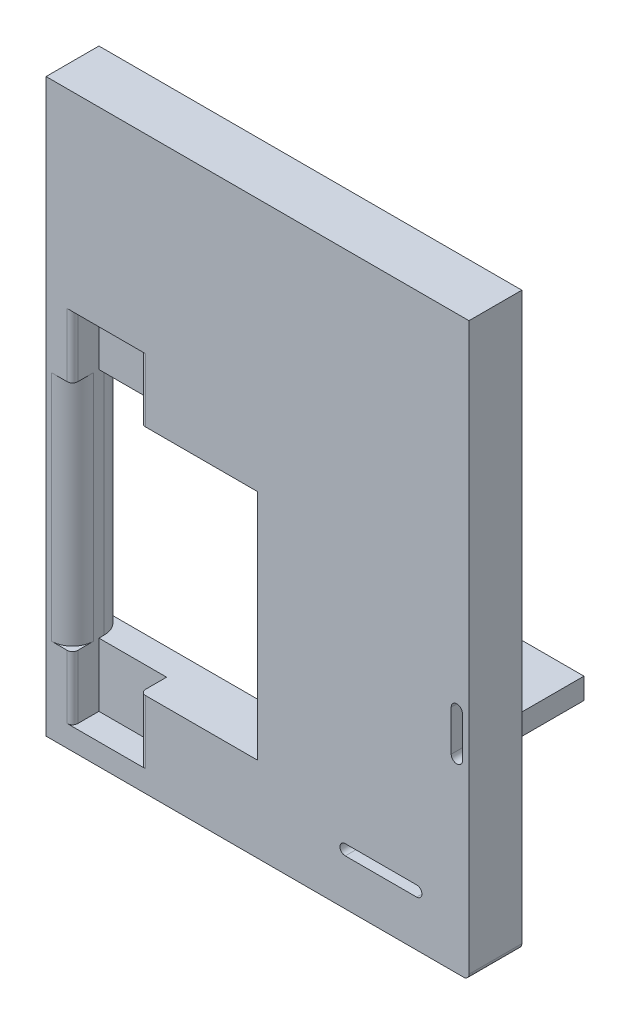
SolidWorks part; units mm, degrees
ref_plane "Front Plane" through (0, 0, 0) normal (0, 0, 1) x (1, 0, 0)
ref_plane "Top Plane" through (0, 0, 0) normal (0, 1, 0) x (1, 0, 0)
ref_plane "Right Plane" through (0, 0, 0) normal (1, 0, 0) x (0, 0, -1)
sketch "Sketch1" plane through (0, 0, 0) normal (0, 0, 1) x (1, 0, 0)
  line L0 (0, -120) -> (87.5104, -120)
  line L1 (100, -120) -> (-100, -120)
  line L2 (100, -120) -> (100, 120)
  line L3 (100, 120) -> (-100, 120)
  line L4 (-100, -120) -> (-100, 120)
  line L7 (0, 0) -> (87.5104, 0)
  line L8 (0, 0) -> (0, -120)
  line L9 (0, -120) -> (87.5104, -120)
  line L10 (87.5104, 0) -> (87.5104, -120)
  point P0 (0, 0)
  dimension "D1" = 240
  dimension "D2" = 200
  dimension "D3" = 87.5104
  dimension "D4" = 120
  dimension "D5" = 100
extrude "Boss-Extrude3" add sketch "Sketch1" along normal blind 25 contours L2 L1 L4 L3
sketch "Sketch3" plane through (0, 0, 25) normal (0, 0, 1) x (1, 0, 0)
  line L5 (-100, -120) -> (-100, 120) construction
  line L6 (0, 0) -> (-87.5, 0)
  line L7 (0, 0) -> (0, -110)
  line L8 (0, -110) -> (-87.5, -110)
  line L9 (-87.5, 0) -> (-87.5, -110)
  line L10 (100, 120) -> (-100, 120) construction
  dimension "D2" = 200
extrude "Cut-Extrude1" cut sketch "Sketch3" against normal blind 25
sketch "Sketch4" plane through (0, 0, 25) normal (0, 0, 1) x (1, 0, 0)
  line L1 (-100, -120) -> (100, -120)
  line L2 (-100, -120) -> (-100, -150.1642)
  line L3 (-100, -150.1642) -> (100, -150.1642)
  line L4 (100, -120) -> (100, -150.1642)
extrude "Boss-Extrude4" add sketch "Sketch4" against normal blind 25
fillet "Fillet4" radius 10 1 edges at (-87.5, -55, 25)
fillet "Fillet5" radius 10 1 edges at (-87.5, -55, 0)
sketch "Sketch6" plane through (0, 0, 25) normal (0, 0, 1) x (1, 0, 0)
  line L1 (-87.5, -110) -> (-55.5, -110)
  line L2 (-87.5, -110) -> (-87.5, -140)
  line L3 (-87.5, -140) -> (-55.5, -140)
  line L4 (-55.5, -110) -> (-55.5, -140)
  dimension "D1" = 30
  dimension "D2" = 32
extrude "Cut-Extrude2" cut sketch "Sketch6" against normal blind 12.5
fillet "Fillet6" radius 2.5 1 edges at (-87.5, -125, 25)
fillet "Fillet7" radius 2.5 1 edges at (-55.5, -125, 25)
fillet "Fillet8" radius 2.5 1 edges at (100, -150.1642, 12.5)
sketch "Sketch7" plane through (0, 0, 25) normal (0, 0, 1) x (1, 0, 0)
  line L0 (-87.5, -55) -> (0, -55) construction
  line L1 (-87.5, 0) -> (-87.5, -110) construction
  line L2 (0, -110) -> (0, 0) construction
ref_plane "Plane1" through (0, -55, 0) normal (0, 1, 0) x (1, 0, 0)
mirror "Mirror1" about plane through (0, -55, 0) normal (0, 1, 0) of "Cut-Extrude2"
sketch "Sketch8" plane through (0, 0, 0) normal (0, 0, -1) x (-1, 0, 0)
  line L1 (-89.3675, -63.394) -> (-16.6491, -63.394)
  line L2 (-89.3675, -63.394) -> (-89.3675, -73.394)
  line L3 (-89.3675, -73.394) -> (-16.6491, -73.394)
  line L4 (-16.6491, -63.394) -> (-16.6491, -73.394)
  dimension "D1" = 10
extrude "Boss-Extrude5" add sketch "Sketch8" along normal blind 40
fillet "Fillet9" radius 2.5 2 edges at (-55.5, 15, 25) (-87.5, 15, 25)
sketch "Sketch9" plane through (0, 0, 0) normal (0, 0, -1) x (-1, 0, 0)
  line L0 (-94.2568, -42.4693) -> (-94.2568, -61.7492) construction
  line L1 (-91.5975, -42.4693) -> (-91.5975, -61.7492)
  line L2 (-96.9161, -42.4693) -> (-96.9161, -61.7492)
  arc A0 (-91.5975, -42.4693) -> (-96.9161, -42.4693) centre (-94.2568, -42.4693) ccw
  arc A1 (-96.9161, -61.7492) -> (-91.5975, -61.7492) centre (-94.2568, -61.7492) ccw
  point P2 (-94.2568, -52.1093)
extrude "Cut-Extrude3" cut sketch "Sketch9" against normal blind 40
sketch "Sketch10" plane through (0, 0, 0) normal (0, 0, -1) x (-1, 0, 0)
  line L0 (-75.2671, -125.9455) -> (-41.4919, -125.9455) construction
  line L1 (-75.2671, -123.4455) -> (-41.4919, -123.4455)
  line L2 (-75.2671, -128.4455) -> (-41.4919, -128.4455)
  arc A0 (-75.2671, -123.4455) -> (-75.2671, -128.4455) centre (-75.2671, -125.9455) ccw
  arc A1 (-41.4919, -128.4455) -> (-41.4919, -123.4455) centre (-41.4919, -125.9455) ccw
  point P2 (-58.3795, -125.9455)
  dimension "D1" = 2.5
extrude "Cut-Extrude4" cut sketch "Sketch10" against normal blind 40
